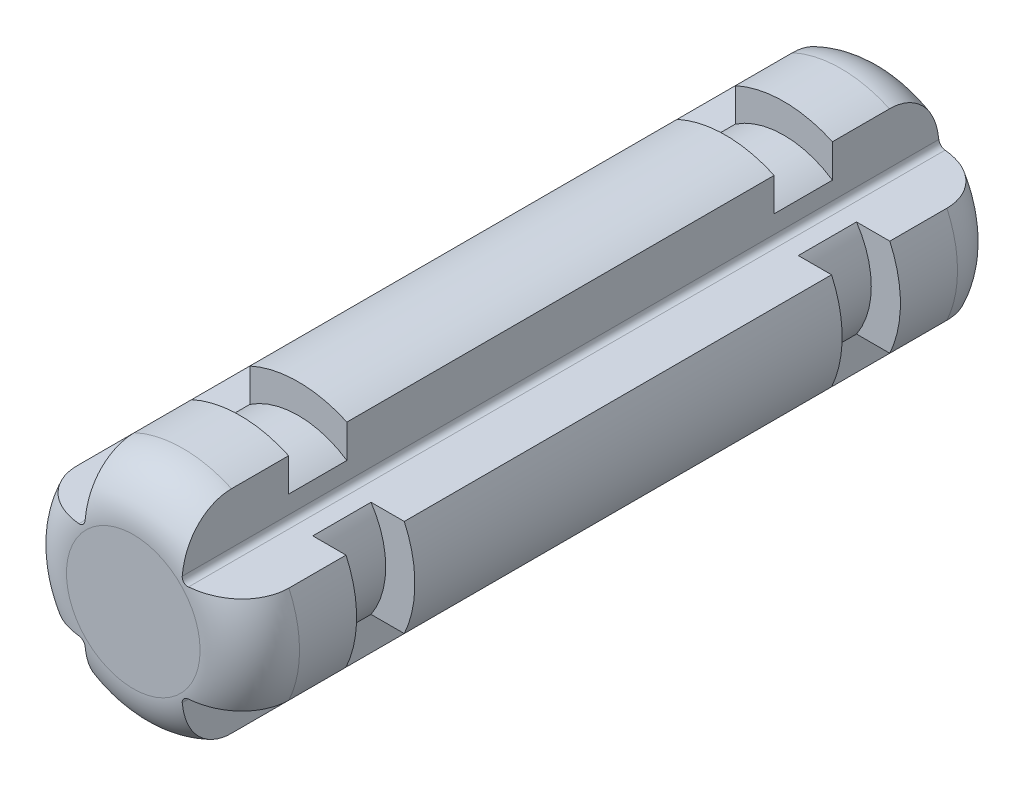
SolidWorks part; units mm, degrees
ref_plane "Front Plane" through (0, 0, 0) normal (0, 0, 1) x (1, 0, 0)
ref_plane "Top Plane" through (0, 0, 0) normal (0, 1, 0) x (1, 0, 0)
ref_plane "Right Plane" through (0, 0, 0) normal (1, 0, 0) x (0, 0, -1)
sketch "Sketch1" plane through (0, 0, 0) normal (0, 0, 1) x (1, 0, 0)
  circle A0 centre (0, 0) radius 2.3813
  dimension "D1" = 4.7625
extrude "Extrude1" add sketch "Sketch1" along normal mid plane 15.4781
fillet "Fillet1" radius 1.016 2 edges at (2.3813, 0, -7.7391) (2.3813, 0, 7.7391)
sketch "Sketch3" plane through (0, 0, 0) normal (0, 0, 1) x (1, 0, 0)
  line L0 (-0.9922, 2.1647) -> (-0.9922, 1.1192)
  line L1 (-1.1192, 0.9922) -> (-2.1647, 0.9922)
  line L2 (-2.1647, -0.9922) -> (-1.1192, -0.9922)
  line L3 (-0.9922, -1.1192) -> (-0.9922, -2.1647)
  line L4 (0.9922, 2.1647) -> (0.9922, 1.1192)
  line L5 (1.1192, 0.9922) -> (2.1647, 0.9922)
  line L6 (0.9922, -1.1192) -> (0.9922, -2.1647)
  line L7 (1.1192, -0.9922) -> (2.1647, -0.9922)
  line L8 (0, 2.3813) -> (0, -2.3813) construction
  line L9 (-2.3813, 0) -> (2.3813, 0) construction
  circle A0 centre (0, 0) radius 2.3813 construction
  arc A1 (-0.9922, 2.1647) -> (-2.1647, 0.9922) centre (0, 0) ccw
  arc A2 (-0.9922, 1.1192) -> (-1.1192, 0.9922) centre (-1.1192, 1.1192) cw
  arc A3 (0.9922, 1.1192) -> (1.1192, 0.9922) centre (1.1192, 1.1192) ccw
  arc A4 (-1.1192, -0.9922) -> (-0.9922, -1.1192) centre (-1.1192, -1.1192) cw
  arc A5 (0.9922, -1.1192) -> (1.1192, -0.9922) centre (1.1192, -1.1192) cw
  arc A6 (2.1647, 0.9922) -> (0.9922, 2.1647) centre (0, 0) ccw
  arc A7 (0.9922, -2.1647) -> (2.1647, -0.9922) centre (0, 0) ccw
  arc A8 (-2.1647, -0.9922) -> (-0.9922, -2.1647) centre (0, 0) ccw
  point P23 (0.9922, 0.9922)
  dimension "D3" = 0.127
  dimension "D1" = 1.9844
  dimension "D2" = 1.9844
extrude "Extrude2" cut sketch "Sketch3" against normal through all and the other way through all
sketch "Sketch4" plane through (0, 0, 0) normal (0, 1, 0) x (1, 0, 0)
  line L0 (-2.3813, 6.7231) -> (-2.3813, -6.7231) construction
  line L1 (-2.3813, 4.3656) -> (-1.7859, 4.3656)
  line L2 (-2.3813, 4.3656) -> (-2.3813, 5.5562)
  line L3 (-2.3813, 5.5562) -> (-1.7859, 5.5562)
  line L4 (-1.7859, 4.3656) -> (-1.7859, 5.5562)
  line L5 (0, 7.7391) -> (0, -7.7391) construction
  line L6 (-2.3813, -5.5562) -> (-1.7859, -5.5562)
  line L7 (-2.3813, -5.5562) -> (-2.3813, -4.3656)
  line L8 (-2.3813, -4.3656) -> (-1.7859, -4.3656)
  line L9 (-1.7859, -5.5562) -> (-1.7859, -4.3656)
  line L10 (1.3653, 7.7391) -> (-1.3653, 7.7391) construction
  line L11 (-1.3653, -7.7391) -> (1.3653, -7.7391) construction
  line L12 (-2.3813, 0) -> (2.1647, 0) construction
  line L13 (2.1647, 6.7231) -> (2.1647, -6.7231) construction
  dimension "D1" = 3.5719
  dimension "D2" = 8.7312
  dimension "D3" = 1.1906
revolve "Cut-Revolve1" cut sketch "Sketch4" angle 360 about L5
